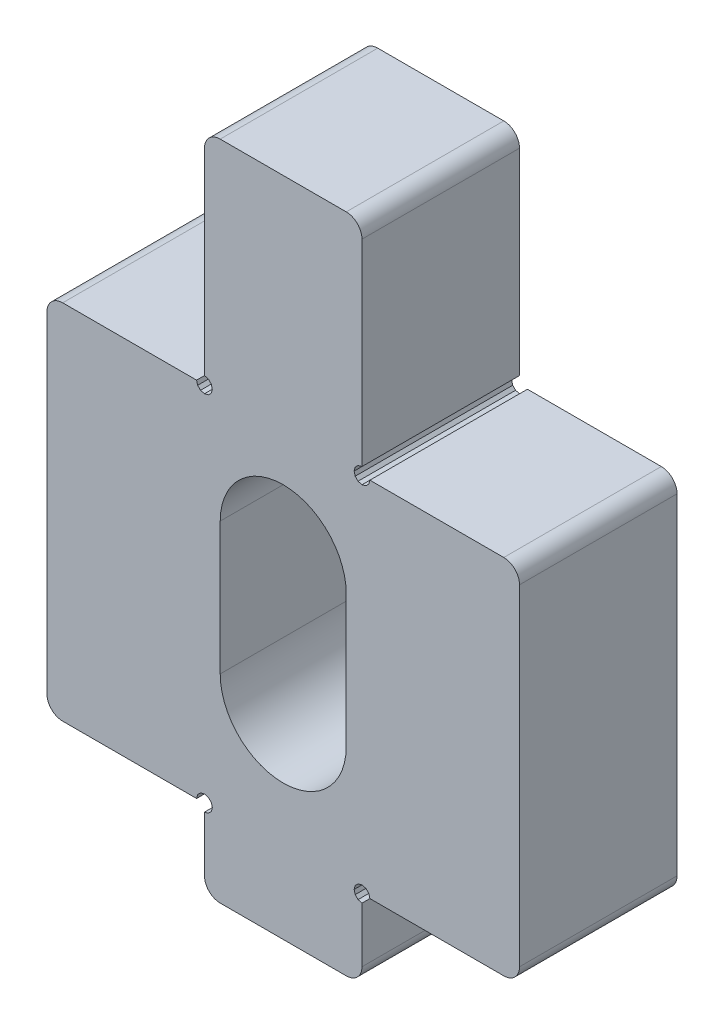
SolidWorks part; units mm, degrees
ref_plane "Plan de face" through (0, 0, 0) normal (0, 0, 1) x (1, 0, 0)
ref_plane "Plan de dessus" through (0, 0, 0) normal (0, 1, 0) x (1, 0, 0)
ref_plane "Plan de droite" through (0, 0, 0) normal (1, 0, 0) x (0, 0, -1)
ref_plane "Plan1" through (0, 0, 5) normal (0, 0, 1) x (1, 0, 0)
sketch "Esquisse1" plane through (0, 0, 5) normal (0, 0, 1) x (1, 0, 0)
  line L0 (5.5, 10.5) -> (5.5, 6.3)
  line L1 (9.5, 10.5) -> (9.5, 6.3)
  line L22 (10, 14.25) -> (10, 20.5)
  line L26 (9.5, 21) -> (5.5, 21)
  line L30 (5, 20.5) -> (5, 14.25)
  line L31 (5, 14.25) -> (5.125, 14.2165)
  line L32 (5.125, 14.2165) -> (5.2165, 14.125)
  line L33 (5.2165, 14.125) -> (5.25, 14)
  line L34 (5.25, 14) -> (5.2165, 13.875)
  line L35 (5.2165, 13.875) -> (5.125, 13.7835)
  line L36 (5.125, 13.7835) -> (5, 13.75)
  line L37 (5, 13.75) -> (4.875, 13.7835)
  line L38 (4.875, 13.7835) -> (4.7835, 13.875)
  line L39 (4.7835, 13.875) -> (4.75, 14)
  line L40 (4.75, 14) -> (0.5, 14)
  line L44 (0, 13.5) -> (0, 3)
  line L48 (0.5, 2.5) -> (4.75, 2.5)
  line L49 (4.75, 2.5) -> (4.7835, 2.625)
  line L50 (4.7835, 2.625) -> (4.875, 2.7165)
  line L51 (4.875, 2.7165) -> (5, 2.75)
  line L52 (5, 2.75) -> (5.125, 2.7165)
  line L53 (5.125, 2.7165) -> (5.2165, 2.625)
  line L54 (5.2165, 2.625) -> (5.25, 2.5)
  line L55 (5.25, 2.5) -> (5.2165, 2.375)
  line L56 (5.2165, 2.375) -> (5.125, 2.2835)
  line L57 (5.125, 2.2835) -> (5, 2.25)
  line L58 (5, 2.25) -> (5, 0.5)
  line L62 (5.5, 0) -> (9.5, 0)
  line L66 (10, 0.5) -> (10, 2.25)
  line L67 (10, 2.25) -> (9.875, 2.2835)
  line L68 (9.875, 2.2835) -> (9.7835, 2.375)
  line L69 (9.7835, 2.375) -> (9.75, 2.5)
  line L70 (9.75, 2.5) -> (9.7835, 2.625)
  line L71 (9.7835, 2.625) -> (9.875, 2.7165)
  line L72 (9.875, 2.7165) -> (10, 2.75)
  line L73 (10, 2.75) -> (10.125, 2.7165)
  line L74 (10.125, 2.7165) -> (10.2165, 2.625)
  line L75 (10.2165, 2.625) -> (10.25, 2.5)
  line L76 (10.25, 2.5) -> (14.5, 2.5)
  line L80 (15, 3) -> (15, 13.5)
  line L84 (14.5, 14) -> (10.25, 14)
  line L85 (10.25, 14) -> (10.2165, 13.875)
  line L86 (10.2165, 13.875) -> (10.125, 13.7835)
  line L87 (10.125, 13.7835) -> (10, 13.75)
  line L88 (10, 13.75) -> (9.875, 13.7835)
  line L89 (9.875, 13.7835) -> (9.7835, 13.875)
  line L90 (9.7835, 13.875) -> (9.75, 14)
  line L91 (9.75, 14) -> (9.7835, 14.125)
  line L92 (9.7835, 14.125) -> (9.875, 14.2165)
  line L93 (9.875, 14.2165) -> (10, 14.25)
  line L94 (7.5, 10.5) -> (7.5, -1.5778) construction
  arc A0 (9.5, 10.5) -> (5.5, 10.5) centre (7.5, 10.5) ccw
  arc A1 (5.5, 6.3) -> (9.5, 6.3) centre (7.5, 6.3) ccw
  arc A2 (5, 20.5) -> (5.5, 21) centre (5.5, 20.5) cw
  arc A3 (9.5, 21) -> (10, 20.5) centre (9.5, 20.5) cw
  arc A4 (0, 13.5) -> (0.5, 14) centre (0.5, 13.5) cw
  arc A5 (14.5, 14) -> (15, 13.5) centre (14.5, 13.5) cw
  arc A6 (0, 3) -> (0.5, 2.5) centre (0.5, 3) ccw
  arc A7 (5, 0.5) -> (5.5, 0) centre (5.5, 0.5) ccw
  arc A8 (9.5, 0) -> (10, 0.5) centre (9.5, 0.5) ccw
  arc A9 (14.5, 2.5) -> (15, 3) centre (14.5, 3) ccw
  dimension "D1" = 4
  dimension "D2" = 4
  dimension "D3" = 4.2
  dimension "D4" = 11.5
  dimension "D5" = 2.5
  dimension "D6" = 3.8
  dimension "D7" = 5
  dimension "D8" = 2.5
  dimension "D9" = 7.5
  dimension "D10" = 15
  dimension "D11" = 15
  dimension "D12" = 2.5
  dimension "D13" = 7
extrude "Boss.-Extru.1" add sketch "Esquisse1" against normal blind 5
